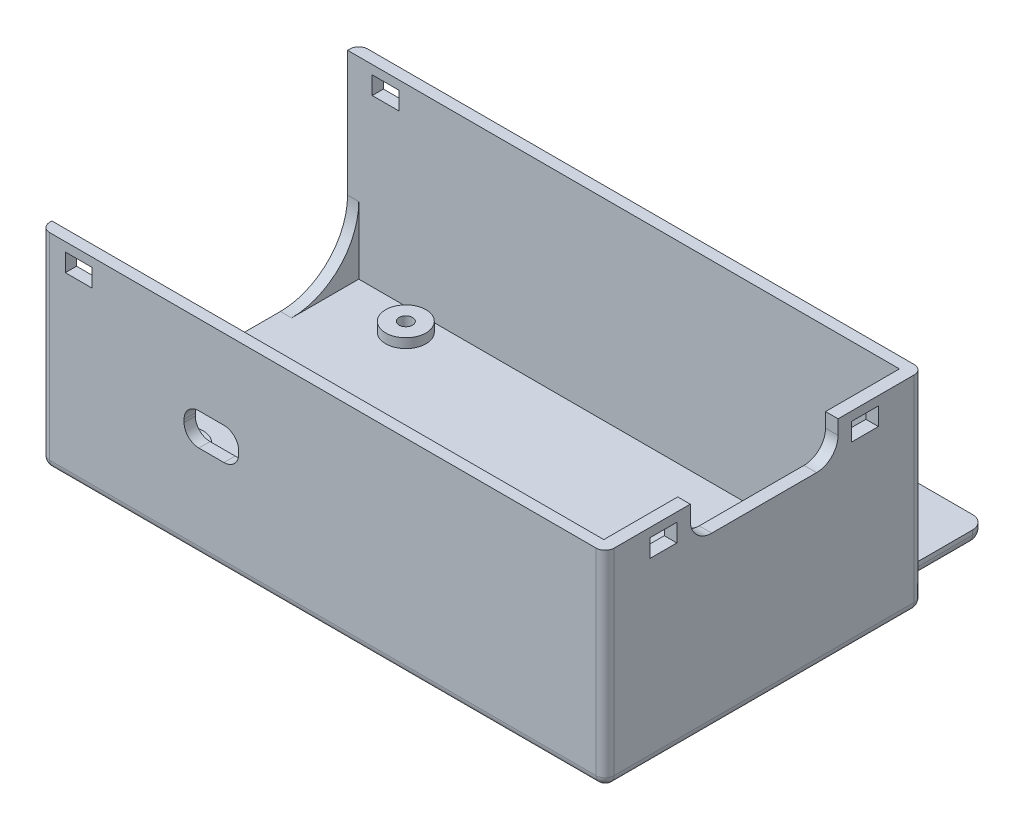
SolidWorks part; units mm, degrees
material "ABS"
ref_plane "Front Plane" through (0, 0, 0) normal (0, 0, 1) x (1, 0, 0)
ref_plane "Top Plane" through (0, 0, 0) normal (0, 1, 0) x (1, 0, 0)
ref_plane "Right Plane" through (0, 0, 0) normal (1, 0, 0) x (0, 0, -1)
sketch "Sketch1" plane through (0, 0, 0) normal (0, 1, 0) x (1, 0, 0)
  line L1 (-63, -35.5) -> (63, -35.5)
  line L2 (-63, -35.5) -> (-63, 35.5)
  line L3 (-63, 35.5) -> (63, 35.5)
  line L4 (63, -35.5) -> (63, 35.5)
  line L5 (-63, -35.5) -> (63, 35.5) construction
  line L6 (-63, 35.5) -> (63, -35.5) construction
  point P0 (0, 0)
  dimension "D1" = 126
  dimension "D2" = 71
extrude "Boss-Extrude1" add sketch "Sketch1" along normal blind 46
sketch "Sketch2" plane through (0, 0, 0) normal (0, -1, 0) x (1, 0, 0)
  line L0 (63, -35.5) -> (-63, -35.5) construction
  line L1 (-56.5, -35.5) -> (-36.5, -35.5)
  line L2 (-56.5, -35.5) -> (-56.5, -56)
  line L3 (-56.5, -56) -> (-36.5, -56)
  line L4 (-36.5, -35.5) -> (-36.5, -56)
  line L5 (63, 35.5) -> (63, -35.5) construction
  line L6 (36.5, -35.5) -> (56.5, -35.5)
  line L7 (36.5, -35.5) -> (36.5, -56)
  line L8 (36.5, -56) -> (56.5, -56)
  line L9 (56.5, -35.5) -> (56.5, -56)
  line L10 (-63, -35.5) -> (-63, 35.5) construction
  dimension "D1" = 20
  dimension "D2" = 20.5
  dimension "D3" = 6.5
  dimension "D4" = 6.5
extrude "Boss-Extrude2" add sketch "Sketch2" against normal blind 3
sketch "Sketch3" plane through (0, 46, 0) normal (0, 1, 0) x (1, 0, 0)
  line L0 (63, 35.5) -> (-63, 35.5) construction
  line L1 (-60.5, 33) -> (60.2, 33)
  line L2 (-60.5, 33) -> (-60.5, -33)
  line L3 (-60.5, -33) -> (60.2, -33)
  line L4 (60.2, 33) -> (60.2, -33)
  line L5 (63, -35.5) -> (63, 35.5) construction
  line L6 (-63, -35.5) -> (63, -35.5) construction
  line L7 (-63, 35.5) -> (-63, -35.5) construction
  dimension "D1" = 2.5
  dimension "D2" = 2.8
  dimension "D3" = 2.5
  dimension "D4" = 2.5
extrude "Cut-Extrude1" cut sketch "Sketch3" against normal blind 43
sketch "Sketch4" plane through (-63, 0, 0) normal (-1, 0, 0) x (0, 0, 1)
  line L0 (-35.5, 46) -> (35.5, 46) construction
  line L1 (-33, 46) -> (33, 46)
  line L2 (-33, 46) -> (-33, 18)
  line L3 (-18, 3) -> (18, 3)
  line L4 (33, 46) -> (33, 18)
  line L5 (33, 3) -> (33, 46) construction
  line L6 (-33, 3) -> (33, 3) construction
  arc A0 (18, 3) -> (33, 18) centre (18, 18) ccw
  arc A1 (-33, 18) -> (-18, 3) centre (-18, 18) ccw
  dimension "D1" = 15
extrude "Cut-Extrude2" cut sketch "Sketch4" against normal up to next
sketch "Sketch5" plane through (63, 0, 0) normal (1, 0, 0) x (0, 0, -1)
  line L0 (-35.5, 46) -> (35.5, 46) construction
  line L1 (-16.5, 46) -> (16.5, 46)
  line L2 (-16.5, 46) -> (-16.5, 42.8)
  line L3 (-11.7, 38) -> (11.7, 38)
  line L4 (16.5, 46) -> (16.5, 42.8)
  line L5 (0, 38) -> (0, 0) construction
  line L6 (19.5, 44) -> (25.5, 44)
  line L7 (19.5, 44) -> (19.5, 40)
  line L8 (19.5, 40) -> (25.5, 40)
  line L9 (25.5, 44) -> (25.5, 40)
  line L10 (-25.5, 44) -> (-19.5, 44)
  line L11 (-25.5, 44) -> (-25.5, 40)
  line L12 (-25.5, 40) -> (-19.5, 40)
  line L13 (-19.5, 44) -> (-19.5, 40)
  arc A0 (11.7, 38) -> (16.5, 42.8) centre (11.7, 42.8) ccw
  arc A1 (-16.5, 42.8) -> (-11.7, 38) centre (-11.7, 42.8) ccw
  point P21 (-16.5, 38)
  dimension "D8" = 4.8
  dimension "D1" = 33
  dimension "D2" = 8
  dimension "D3" = 6
  dimension "D4" = 4
  dimension "D5" = 3
  dimension "D6" = 2
  dimension "D7" = 3
extrude "Cut-Extrude3" cut sketch "Sketch5" against normal up to next
sketch "Sketch6" plane through (0, 0, 35.5) normal (0, 0, 1) x (1, 0, 0)
  line L0 (-63, 46) -> (63, 46) construction
  line L1 (-57.5, 44) -> (-51.5, 44)
  line L2 (-57.5, 44) -> (-57.5, 40)
  line L3 (-57.5, 40) -> (-51.5, 40)
  line L4 (-51.5, 44) -> (-51.5, 40)
  line L5 (-63, 46) -> (-63, 0) construction
  dimension "D1" = 6
  dimension "D2" = 4
  dimension "D3" = 2
  dimension "D4" = 5.5
extrude "Cut-Extrude4" cut sketch "Sketch6" against normal through all
sketch "Sketch7" plane through (0, 0, 35.5) normal (0, 0, 1) x (1, 0, 0)
  line L0 (-63, 46) -> (63, 46) construction
  line L1 (-27.7, 28.2) -> (-22.1, 28.2)
  line L2 (-31, 24.9) -> (-31, 24.3)
  line L3 (-27.7, 21) -> (-22.1, 21)
  line L4 (-18.8, 24.9) -> (-18.8, 24.3)
  line L5 (-63, 46) -> (-63, 0) construction
  arc A0 (-22.1, 28.2) -> (-18.8, 24.9) centre (-22.1, 24.9) cw
  arc A1 (-22.1, 21) -> (-18.8, 24.3) centre (-22.1, 24.3) ccw
  arc A2 (-31, 24.3) -> (-27.7, 21) centre (-27.7, 24.3) ccw
  arc A3 (-27.7, 28.2) -> (-31, 24.9) centre (-27.7, 24.9) ccw
  point P10 (-18.8, 28.2)
  point P15 (-31, 21)
  point P18 (-31, 28.2)
  dimension "D5" = 3.3
  dimension "D1" = 7.2
  dimension "D2" = 12.2
  dimension "D3" = 17.8
  dimension "D4" = 32
extrude "Cut-Extrude5" cut sketch "Sketch7" against normal up to next
sketch "Sketch8" plane through (0, 3, 0) normal (0, 1, 0) x (1, 0, 0)
  line L0 (-56.5, 56) -> (-36.5, 56) construction
  line L1 (-46.5, 46) -> (-46.5, 56) construction
  line L2 (46.5, 56) -> (46.5, 46) construction
  line L3 (36.5, 56) -> (56.5, 56) construction
  circle A0 centre (-46.5, 46) radius 2.4
  circle A1 centre (46.5, 46) radius 2.4
  dimension "D1" = 4.8
  dimension "D2" = 10
extrude "Cut-Extrude6" cut sketch "Sketch8" against normal through all
fillet "Fillet1" radius 3 4 edges at (36.5, 1.5, -56) (56.5, 1.5, -56) (-36.5, 1.5, -56) (-56.5, 1.5, -56)
fillet "Fillet2" radius 4 4 edges at (56.5, 1.5, -35.5) (36.5, 1.5, -35.5)
fillet "Fillet3" radius 2 24 edges at (-63, 23, 35.5) (-63, 23, -35.5) (63, 23, -35.5) (63, 23, 35.5) (-57.6716, 0, -36.6716) (-55.6213, 0, -55.1213) (-46.5, 0, -56) (-37.3787, 0, -55.1213) (-35.3284, 0, -36.6716) (35.3284, 0, -36.6716) (36.5, 0, -46.25) (37.3787, 0, -55.1213) (46.5, 0, -56) (55.6213, 0, -55.1213) (56.5, 0, -46.25) (57.6716, 0, -36.6716) (63, 0, 0) (0, 0, 35.5) (-63, 0, 0)
sketch "Sketch9" plane through (0, 3, 0) normal (0, 1, 0) x (1, 0, 0)
  line L0 (-53.5, 56) -> (-39.5, 56) construction
  line L1 (-56.5, 39.5) -> (-56.5, 53) construction
  circle A0 centre (-45, 28) radius 4.5
  circle A1 centre (-46.4, -20.3) radius 4.5
  circle A2 centre (31, 18) radius 4.5
  circle A3 centre (36.6, -20.3) radius 4.5
  dimension "D1" = 9
  dimension "D2" = 28
  dimension "D3" = 11.5
  dimension "D4" = 10.1
  dimension "D5" = 76.3
  dimension "D9" = 93.1
  dimension "D6" = 38
  dimension "D7" = 87.5
  dimension "D8" = 76.3
extrude "Boss-Extrude3" add sketch "Sketch9" along normal blind 2.1
sketch "Sketch10" plane through (0, 5.1, 0) normal (0, 1, 0) x (1, 0, 0)
  circle A0 centre (-45, 28) radius 1.5
  circle A1 centre (-46.4, -20.3) radius 1.5
  circle A2 centre (36.6, -20.3) radius 1.5
  dimension "D1" = 3
extrude "Cut-Extrude7" cut sketch "Sketch10" against normal through all
